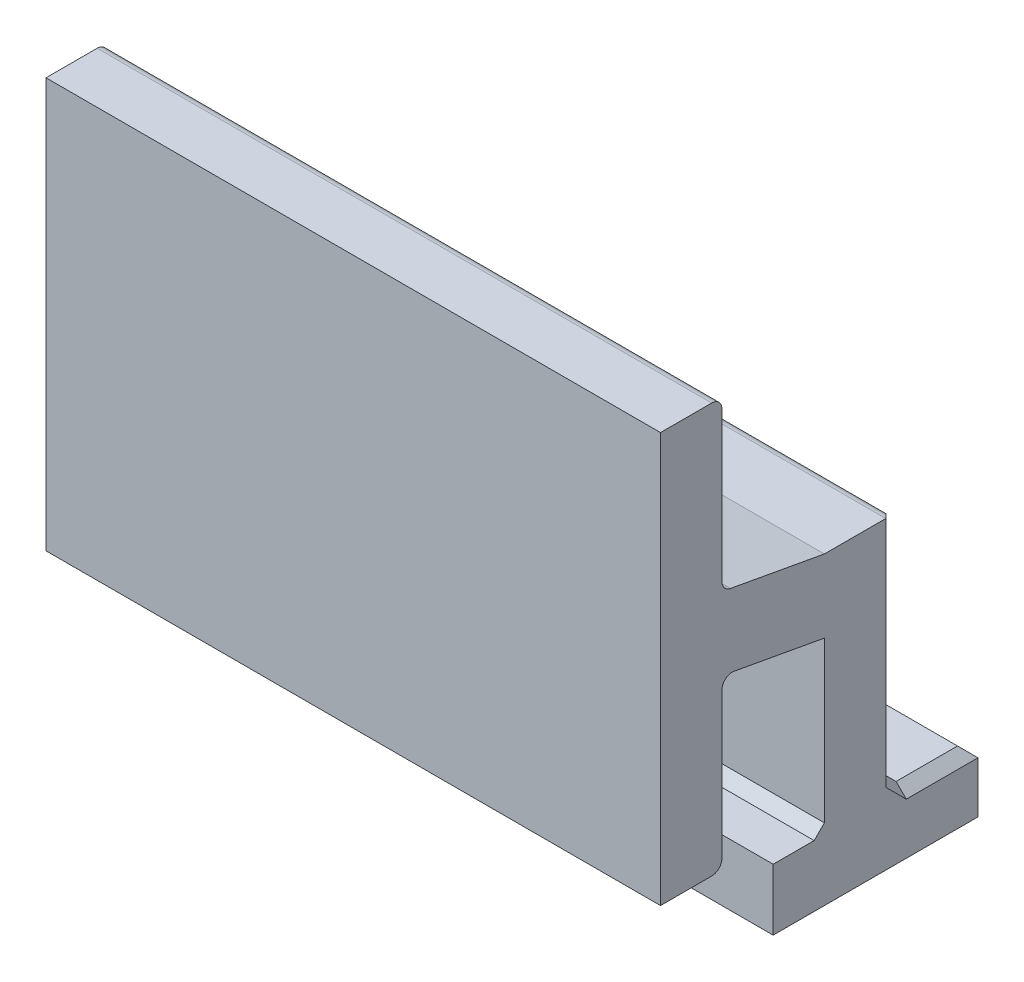
SolidWorks part; units mm, degrees
ref_plane "Front Plane" through (0, 0, 0) normal (0, 0, 1) x (1, 0, 0)
ref_plane "Top Plane" through (0, 0, 0) normal (0, 1, 0) x (1, 0, 0)
ref_plane "Right Plane" through (0, 0, 0) normal (1, 0, 0) x (0, 0, -1)
sketch "Sketch1" plane through (0, 0, 0) normal (1, 0, 0) x (0, 0, -1)
  line L1 (-5, 0) -> (-5, 3)
  line L2 (-5, 3) -> (-2.5, 3)
  line L3 (-2.5, 3) -> (-2.5, 11.3097)
  line L4 (-2.5, 11.3097) -> (-7.5, 12.2212)
  line L5 (-7.5, 12.2212) -> (-7.5, 4)
  line L6 (-7.5, 4) -> (-10.5, 4)
  line L7 (-10.5, 4) -> (-10.5, 24)
  line L8 (-10.5, 24) -> (-7.5, 24)
  line L9 (-7.5, 24) -> (-7.5, 15.7788)
  line L10 (-7.5, 15.7788) -> (-2.5, 14.8674)
  line L11 (-2.5, 14.8674) -> (1, 14.8674)
  line L12 (1, 14.8674) -> (1, 3)
  line L13 (1, 3) -> (5, 3)
  line L14 (5, 3) -> (5, 0)
  line L16 (-5, 0) -> (5, 0)
  point P0 (0, 0)
  dimension "D1" = 3
  dimension "D2" = 10
  dimension "D3" = 3.5
  dimension "D4" = 3.5
  dimension "D5" = 3
  dimension "D6" = 20
  dimension "D7" = 4
  dimension "D8" = 3.5
  dimension "D9" = 3.5577
  dimension "D10" = 5
  dimension "D11" = 1
extrude "Boss-Extrude1" add sketch "Sketch1" along normal blind 30
chamfer "Chamfer1" distance 0.5 angle 45 7 edges at (15, 3, 2.5) (0, 3, -3) (30, 8.9337, -1) (0, 8.9337, -1) (15, 3, -5) (30, 3, -3) (15, 3, -1)
fillet "Fillet1" radius 0.5 5 edges at (15, 4, 7.5) (15, 24, 7.5) (15, 12.2212, 7.5) (15, 15.7788, 7.5) (15, 14.8674, -1)
sketch "Sketch2" plane through (30, 0, 0) normal (1, 0, 0) x (0, 0, -1)
  line L0 (-7.5, 16.1959) -> (-7.5, 11.6218)
  line L17 (-10.5, 4) -> (-8, 4)
  line L18 (-7.5, 4.5) -> (-7.5, 11.6218)
  line L19 (-6.9103, 12.1137) -> (-2.5, 11.3097)
  line L20 (-2.5, 11.3097) -> (-2.5, 3.5)
  line L21 (-2.5, 3.5) -> (-3, 3)
  line L22 (-5, 3) -> (-5, 0)
  line L23 (-5, 0) -> (5, 0)
  line L24 (5, 0) -> (5, 2.5)
  line L25 (5, 2.5) -> (1.5, 2.5)
  line L26 (1.5, 2.5) -> (1, 3)
  line L27 (1, 3) -> (0.5, 3.5)
  line L28 (0.5, 3.5) -> (0.5, 14.8674)
  line L29 (0.5, 14.8674) -> (-2.5, 14.8674)
  line L30 (-2.5, 14.8674) -> (-7.0897, 15.704)
  line L31 (-7.5, 16.1959) -> (-7.5, 23.5)
  line L32 (-8, 24) -> (-10.5, 24)
  line L33 (-10.5, 24) -> (-10.5, 4)
  line L34 (-10.5, 4) -> (-8, 4)
  line L35 (-7.5, 4.5) -> (-7.5, 11.6218)
  line L48 (-7.5, 16.1959) -> (-7.5, 23.5)
  line L49 (-8, 24) -> (-10.5, 24)
  line L50 (-10.5, 24) -> (-10.5, 4)
  line L53 (-3, 3) -> (-5, 3)
  arc A4 (-8, 4) -> (-7.5, 4.5) centre (-8, 4.5) ccw
  arc A5 (-6.9103, 12.1137) -> (-7.5, 11.6218) centre (-7, 11.6218) ccw
  arc A6 (-7.5, 16.1959) -> (-7.0897, 15.704) centre (-7, 16.1959) ccw
  arc A7 (-7.5, 23.5) -> (-8, 24) centre (-8, 23.5) ccw
  arc A8 (-8, 4) -> (-7.5, 4.5) centre (-8, 4.5) ccw
  arc A11 (-7.5, 23.5) -> (-8, 24) centre (-8, 23.5) ccw
  dimension "D1" = 0
ref_plane "Plane1" through (15, 0, 0) normal (-1, 0, 0) x (0, 0, 1)
